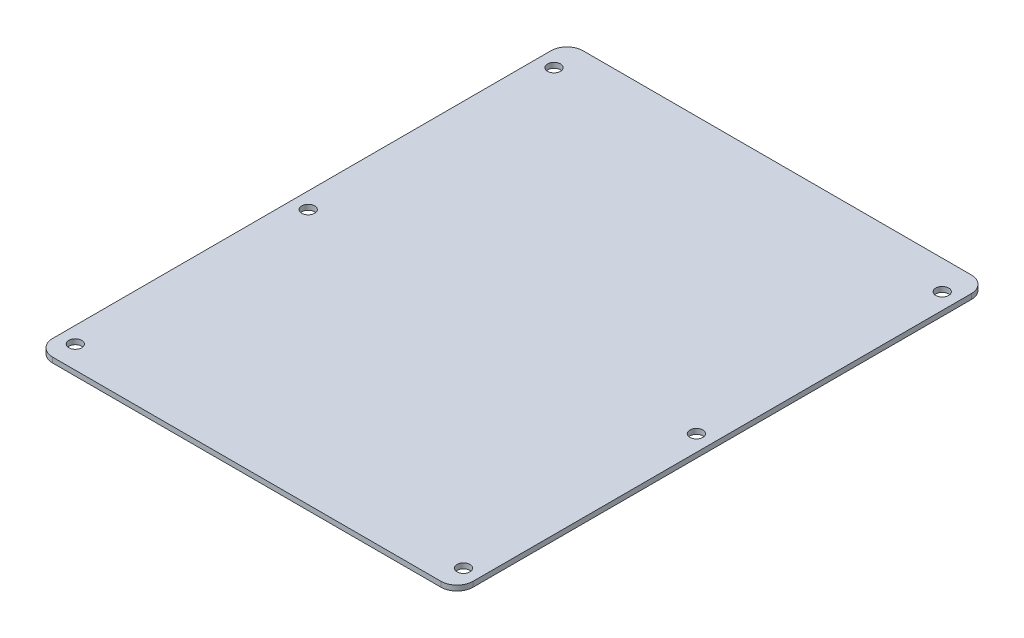
SolidWorks part; units mm, degrees
material "3003-H16"
ref_plane "Plan de face" through (0, 0, 0) normal (0, 0, 1) x (1, 0, 0)
ref_plane "Plan de dessus" through (0, 0, 0) normal (0, 1, 0) x (1, 0, 0)
ref_plane "Plan de droite" through (0, 0, 0) normal (1, 0, 0) x (0, 0, -1)
sketch "Esquisse1" plane through (0, 0, 0) normal (0, 1, 0) x (1, 0, 0)
  line L1 (-65, 82) -> (65, 82)
  line L2 (-65, 82) -> (-65, -82)
  line L3 (-65, -82) -> (65, -82)
  line L4 (65, 82) -> (65, -82)
  line L5 (-65, 82) -> (65, -82) construction
  line L6 (-65, -82) -> (65, 82) construction
  point P0 (0, 0)
  dimension "D1" = 164
  dimension "D2" = 130
extrude "Boss.-Extru.1" add sketch "Esquisse1" along normal blind 1.6
sketch "Esquisse2" plane through (0, 1.6, 0) normal (0, 1, 0) x (1, 0, 0)
  line L0 (-60, 82) -> (-60, 73) construction
  line L1 (65, 82) -> (-65, 82) construction
  line L2 (-65, 73) -> (-60, 73) construction
  line L3 (-65, 82) -> (-65, -82) construction
  line L4 (-60, 73) -> (-60, -3) construction
  line L5 (-60, -82) -> (-60, -75) construction
  line L6 (-65, -82) -> (65, -82) construction
  line L7 (0, 0) -> (0, 82) construction
  circle A0 centre (-60, 73) radius 2
  circle A1 centre (-60, -3) radius 2
  circle A2 centre (-60, -75) radius 2
  circle A3 centre (60, -75) radius 2
  circle A4 centre (60, -3) radius 2
  circle A5 centre (60, 73) radius 2
  dimension "D3" = 4
  dimension "D5" = 4
  dimension "D7" = 4
  dimension "D1" = 148
  dimension "D2" = 5
  dimension "D4" = 76
extrude "Enlèv. mat.-Extru.1" cut sketch "Esquisse2" against normal through all
fillet "Congé1" radius 5 4 edges at (65, 0.8, -82) (-65, 0.8, -82) (-65, 0.8, 82) (65, 0.8, 82)
